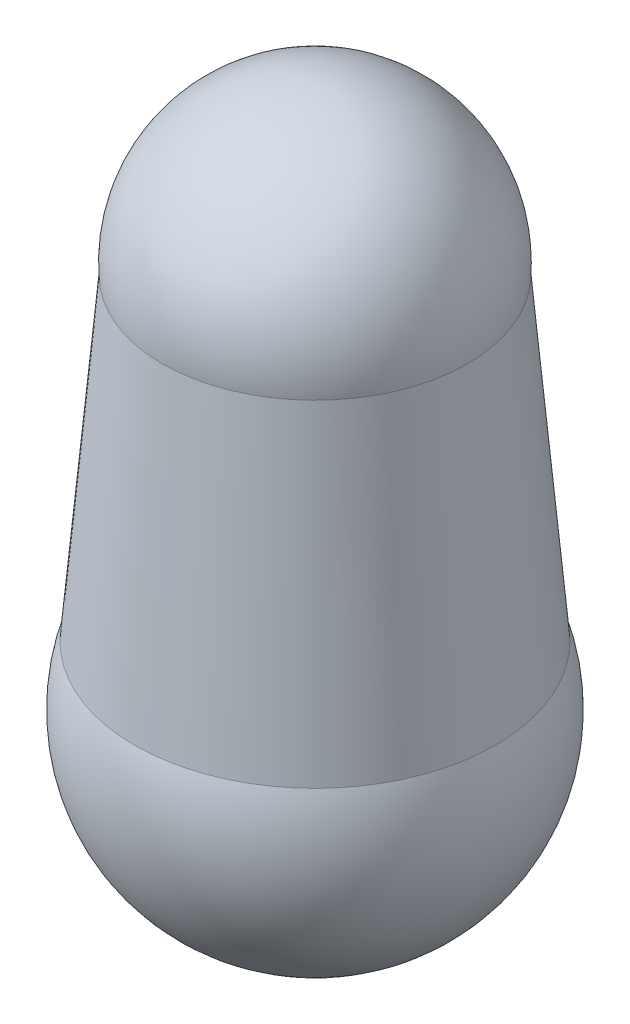
SolidWorks part; units mm, degrees
ref_plane "Front Plane" through (0, 0, 0) normal (0, 0, 1) x (1, 0, 0)
ref_plane "Top Plane" through (0, 0, 0) normal (0, 1, 0) x (1, 0, 0)
ref_plane "Right Plane" through (0, 0, 0) normal (1, 0, 0) x (0, 0, -1)
sketch "Sketch1" plane through (0, 0, 0) normal (0, 1, 0) x (1, 0, 0)
  line L0 (0, 4.9) -> (0, -4.9) construction
  line L1 (0, 4.9) -> (0, -4.9)
  arc A0 (0, -4.9) -> (0, 4.9) centre (0, 0) ccw
  dimension "D1" = 9.8
revolve "Revolve1" add sketch "Sketch1" angle 360 about L0
sketch "Sketch2" plane through (0, 0, 0) normal (0, 1, 0) x (1, 0, 0)
  circle A0 centre (0, 0) radius 4.7889
extrude "Boss-Extrude1" add sketch "Sketch2" along normal blind 10 draft 5
sketch "Sketch3" plane through (0, 10, 0) normal (0, 1, 0) x (1, 0, 0)
  line L0 (0, 3.9514) -> (0, -3.9514) construction
  line L1 (0, 3.9514) -> (0, -3.9514)
  arc A0 (0, -3.9514) -> (0, 3.9514) centre (0, 0) ccw
revolve "Revolve2" add sketch "Sketch3" angle 360 about L0
